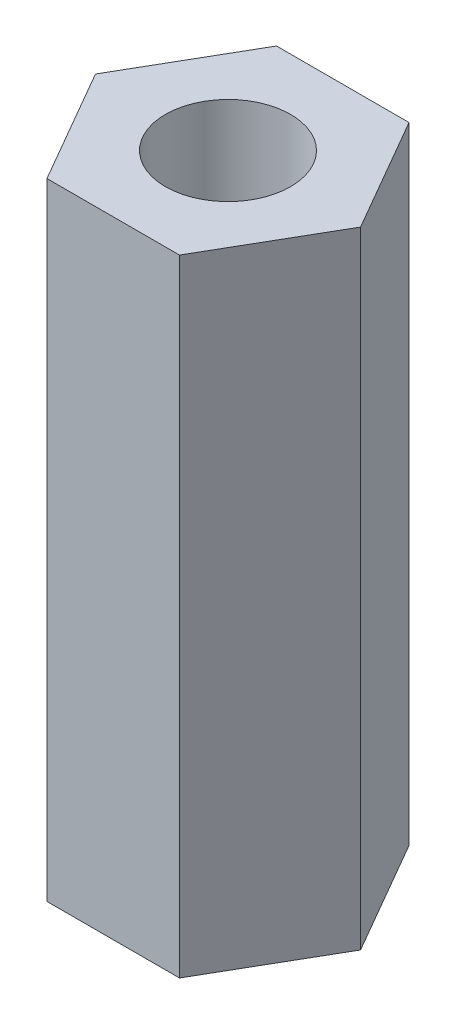
SolidWorks part; units mm, degrees
ref_plane "Front Plane" through (0, 0, 0) normal (0, 0, 1) x (1, 0, 0)
ref_plane "Top Plane" through (0, 0, 0) normal (0, 1, 0) x (1, 0, 0)
ref_plane "Right Plane" through (0, 0, 0) normal (1, 0, 0) x (0, 0, -1)
sketch "Sketch1" plane through (0, 0, 0) normal (0, 1, 0) x (1, 0, 0)
  line L1 (3.1754, 0) -> (1.5877, 2.75)
  line L2 (1.5877, 2.75) -> (-1.5877, 2.75)
  line L3 (-1.5877, 2.75) -> (-3.1754, 0)
  line L4 (-3.1754, 0) -> (-1.5877, -2.75)
  line L5 (-1.5877, -2.75) -> (1.5877, -2.75)
  line L6 (1.5877, -2.75) -> (3.1754, 0)
  circle A0 centre (0, 0) radius 2.75 construction
  dimension "D1" = 5.5
extrude "Boss-Extrude1" add sketch "Sketch1" along normal blind 15
sketch "Sketch2" plane through (0, 15, 0) normal (0, 1, 0) x (1, 0, 0)
  circle A0 centre (0, 0) radius 1.5
  dimension "D1" = 3
extrude "Cut-Extrude1" cut sketch "Sketch2" against normal blind 10
ref_plane "Plane1" through (0, 7.5, 0) normal (0, -1, 0) x (-1, 0, 0)
mirror "Mirror1" about plane through (0, 7.5, 0) normal (0, -1, 0) of "Cut-Extrude1"
